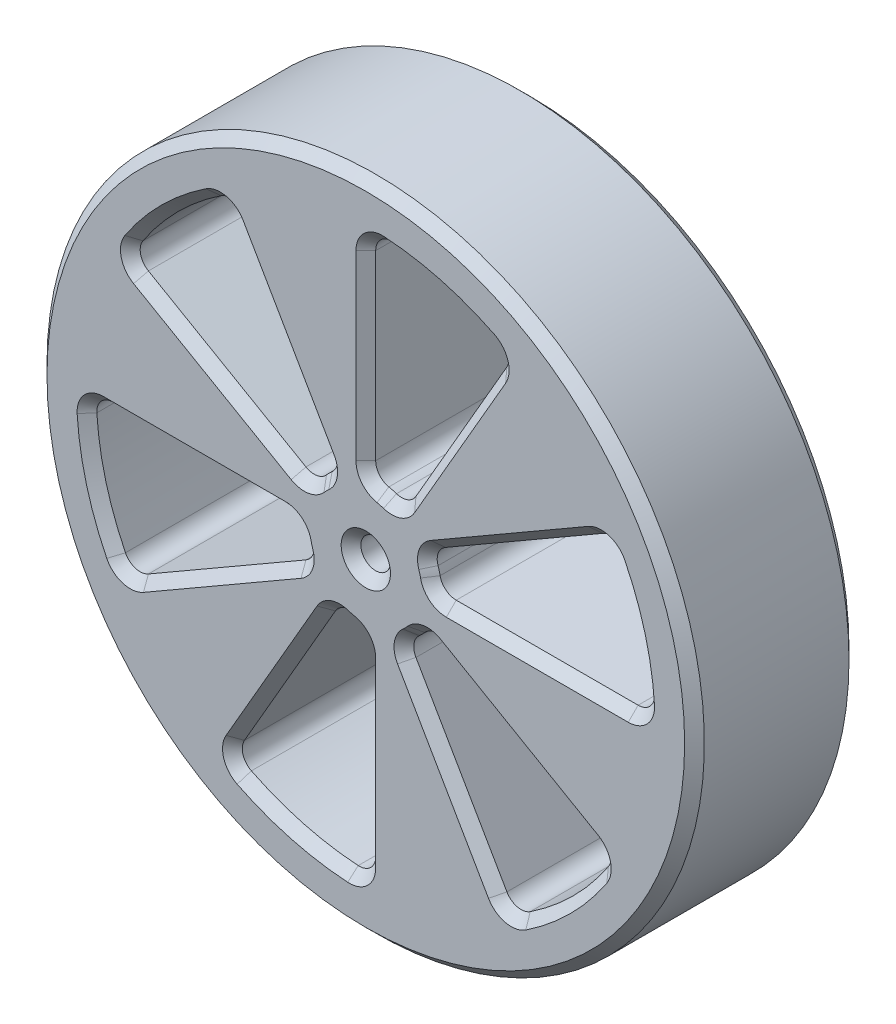
SolidWorks part; units mm, degrees
ref_plane "Front Plane" through (0, 0, 0) normal (0, 0, 1) x (1, 0, 0)
ref_plane "Top Plane" through (0, 0, 0) normal (0, 1, 0) x (1, 0, 0)
ref_plane "Right Plane" through (0, 0, 0) normal (1, 0, 0) x (0, 0, -1)
sketch "Sketch1" plane through (0, 0, 0) normal (0, 0, 1) x (1, 0, 0)
  circle A0 centre (0, 0) radius 100
  dimension "D1" = 200
extrude "Boss-Extrude1" add sketch "Sketch1" along normal blind 50
sketch "Sketch2" plane through (0, 0, 50) normal (0, 0, 1) x (1, 0, 0)
  line L0 (0, 20) -> (0, 85)
  line L1 (10, 17.3205) -> (42.5, 73.6122)
  circle A0 centre (0, 0) radius 20
  circle A1 centre (0, 0) radius 85
  circle A2 centre (0, 0) radius 100 construction
  dimension "D1" = 40
  dimension "D2" = 15
  dimension "D3" = 30
extrude "Cut-Extrude1" cut sketch "Sketch2" against normal through all contours L1 A1 L0 A0
pattern_circular "CirPattern1" count 6 over 360 about axis through (0, 0, 0) along (0, 0, 1) of "Cut-Extrude1"
fillet "Fillet1" radius 5 24 edges at (0, 85, 25) (42.5, 73.6122, 25) (10, 17.3205, 25) (-17.3205, 10, 25) (-73.6122, 42.5, 25) (-42.5, 73.6122, 25) (-10, 17.3205, 25) (0, -20, 25) (0, -85, 25) (-42.5, -73.6122, 25) (-10, -17.3205, 25) (-17.3205, -10, 25) (-73.6122, -42.5, 25) (-85, 0, 25) (-20, 0, 25) (17.3205, -10, 25) (73.6122, -42.5, 25) (42.5, -73.6122, 25) (10, -17.3205, 25) (17.3205, 10, 25) (73.6122, 42.5, 25) (85, 0, 25) (20, 0, 25) (0, 20, 25)
sketch "Sketch3" plane through (0, 0, 50) normal (0, 0, 1) x (1, 0, 0)
  line L1 (0, 0) -> (0, -4.5) construction
  circle A0 centre (0, 0) radius 4.5
  dimension "D1" = 9
extrude "Cut-Extrude2" cut sketch "Sketch3" against normal through all
chamfer "Chamfer1" distance 3 angle 45 100 edges at (100, 0, 50) (40.3785, 73.091, 50) (21.9996, 82.1037, 50) (1.5767, 83.4879, 50) (0, 52.1692, 50) (1.127, 21.3326, 50) (5.1764, 19.3185, 50) (9.6903, 19.0381, 50) (26.0846, 45.1799, 50) (-43.1095, 71.5143, 50) (-60.1041, 60.1041, 50) (-71.5143, 43.1095, 50) (-45.1799, 26.0846, 50) (-17.9111, 11.6423, 50) (-14.1421, 14.1421, 50) (-11.6423, 17.9111, 50) (-26.0846, 45.1799, 50) (-40.3785, -73.091, 50) (-21.9996, -82.1037, 50) (-1.5767, -83.4879, 50) (0, -52.1692, 50) (-1.127, -21.3326, 50) (-5.1764, -19.3185, 50) (-9.6903, -19.0381, 50) (-26.0846, -45.1799, 50) (-83.4879, -1.5767, 50) (-82.1037, -21.9996, 50) (-73.091, -40.3785, 50) (-45.1799, -26.0846, 50) (-19.0381, -9.6903, 50) (-19.3185, -5.1764, 50) (-21.3326, -1.127, 50) (-52.1692, 0, 50) (43.1095, -71.5143, 50) (60.1041, -60.1041, 50) (71.5143, -43.1095, 50) (45.1799, -26.0846, 50) (17.9111, -11.6423, 50) (14.1421, -14.1421, 50) (11.6423, -17.9111, 50) (26.0846, -45.1799, 50) (83.4879, 1.5767, 50) (82.1037, 21.9996, 50) (73.091, 40.3785, 50) (45.1799, 26.0846, 50) (19.0381, 9.6903, 50) (19.3185, 5.1764, 50) (21.3326, 1.127, 50) (52.1692, 0, 50) (4.5, 0, 50) (100, 0, 0) (1.127, 21.3326, 0) (0, 52.1692, 0) (1.5767, 83.4879, 0) (21.9996, 82.1037, 0) (40.3785, 73.091, 0) (26.0846, 45.1799, 0) (9.6903, 19.0381, 0) (5.1764, 19.3185, 0) (-17.9111, 11.6423, 0) (-45.1799, 26.0846, 0) (-71.5143, 43.1095, 0) (-60.1041, 60.1041, 0) (-43.1095, 71.5143, 0) (-26.0846, 45.1799, 0) (-11.6423, 17.9111, 0) (-14.1421, 14.1421, 0) (-1.127, -21.3326, 0) (0, -52.1692, 0) (-1.5767, -83.4879, 0) (-21.9996, -82.1037, 0) (-40.3785, -73.091, 0) (-26.0846, -45.1799, 0) (-9.6903, -19.0381, 0) (-5.1764, -19.3185, 0) (-19.0381, -9.6903, 0) (-45.1799, -26.0846, 0) (-73.091, -40.3785, 0) (-82.1037, -21.9996, 0) (-83.4879, -1.5767, 0) (-52.1692, 0, 0) (-21.3326, -1.127, 0) (-19.3185, -5.1764, 0) (17.9111, -11.6423, 0) (45.1799, -26.0846, 0) (71.5143, -43.1095, 0) (60.1041, -60.1041, 0) (43.1095, -71.5143, 0) (26.0846, -45.1799, 0) (11.6423, -17.9111, 0) (14.1421, -14.1421, 0) (19.0381, 9.6903, 0) (45.1799, 26.0846, 0) (73.091, 40.3785, 0) (82.1037, 21.9996, 0) (83.4879, 1.5767, 0) (52.1692, 0, 0) (21.3326, 1.127, 0) (19.3185, 5.1764, 0) (4.5, 0, 0)
